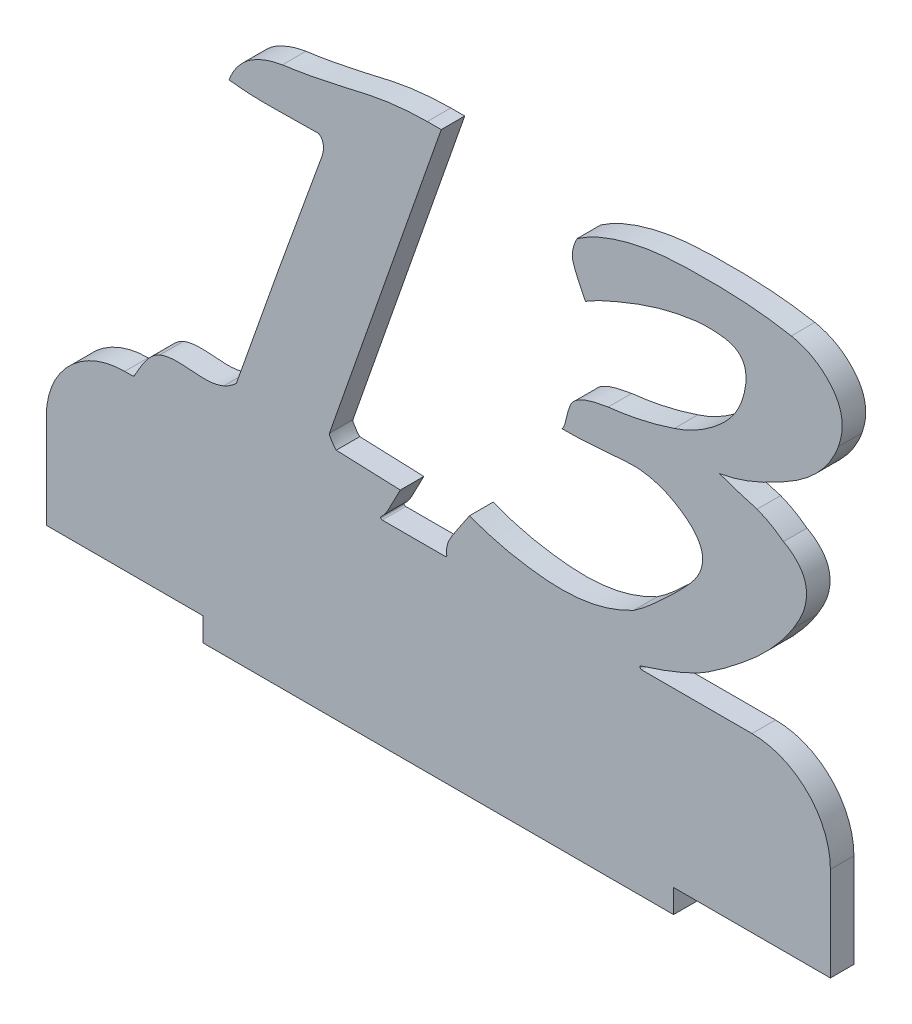
SolidWorks part; units mm, degrees
ref_plane "Front Plane" through (0, 0, 0) normal (0, 0, 1) x (1, 0, 0)
ref_plane "Top Plane" through (0, 0, 0) normal (0, 1, 0) x (1, 0, 0)
ref_plane "Right Plane" through (0, 0, 0) normal (1, 0, 0) x (0, 0, -1)
sketch "Sketch1" plane through (0, 0, 0) normal (0, 0, 1) x (1, 0, 0)
  line L0 (0, 20) -> (100, 20) construction
  line L1 (42.2093, 22) -> (51.1251, 22)
  line L2 (0, 22) -> (0, 0)
  line L3 (0, 0) -> (20, 0)
  line L4 (100, 22) -> (100, 0)
  line L5 (0, 22) -> (11.1488, 22)
  line L6 (90.1102, 22) -> (100, 22)
  line L7 (50.3695, 68.8865) -> (36.1201, 28.2493)
  line L8 (36.9802, 26.7833) -> (45.1506, 26.4705)
  line L9 (74.5438, 22) -> (90.1102, 22)
  line L11 (80, 0) -> (100, 0)
  line L13 (20, 0) -> (20, -3)
  line L14 (20, -3) -> (80, -3)
  line L15 (80, 0) -> (80, -3)
  spline S0 degree 3 poles (45.1506, 26.4705) (44.5557, 25.4573) (44.0105, 24.1351) (43.1126, 22.6689) (42.6125, 22.2566) (42.2988, 22.0538) (42.2093, 22) knots 0 0 0 0 0.504343 0.619768 0.735364 0.780343 0.780343 0.780343 0.780343
  spline S1 degree 3 poles (11.1488, 22) (11.2941, 22.2364) (11.6816, 22.909) (12.5467, 24.461) (13.5414, 25.6306) (14.4821, 26.06) knots 0.109992 0.109992 0.109992 0.109992 0.248912 0.498933 1 1 1 1
  spline S2 degree 3 poles (14.4821, 26.06) (15.8235, 26.5793) (18.5742, 26.3045) (21.3436, 26.1489) (22.6526, 26.7246) knots 0 0 0 0 0.501452 1 1 1 1
  spline S3 degree 2 poles (22.6526, 26.7246) (23.5341, 27.1151) (24.2358, 27.7801) knots 0 0 0 1 1 1
  spline S4 degree 3 poles (24.2358, 27.7801) (26.0181, 32.8153) (29.5431, 42.9381) (33.2322, 53.0023) (35.0646, 58.0577) knots 0 0 0 0 0.498323 1 1 1 1
  spline S5 degree 3 poles (35.0646, 58.0577) (35.2478, 58.5552) (35.543, 59.5218) (35.0904, 60.4332) (34.7323, 60.6378) knots 0 0 0 0 0.581397 1 1 1 1
  spline S6 degree 3 poles (34.7323, 60.6378) (32.8156, 60.6716) (29.0106, 60.4877) (25.1976, 60.5925) (23.3172, 60.8333) knots 0 0 0 0 0.503015 1 1 1 1
  spline S7 degree 3 poles (23.3172, 60.8333) (23.5491, 61.5005) (24.0334, 62.4494) (24.9514, 63.5102) (25.7246, 64.2327) (26.6726, 64.7864) (28.0996, 65.4691) (29.2917, 65.7839) (30.1194, 65.9154) knots 0 0 0 0 0.237267 0.352024 0.469659 0.590381 0.718477 1 1 1 1
  spline S8 degree 3 poles (30.1194, 65.9154) (33.2316, 66.3138) (37.0934, 67.1658) (41.7152, 68.2457) (44.7951, 68.7281) (47.0882, 68.8757) (48.5908, 68.8865) knots 0 0 0 0 0.501478 0.63281 0.759518 1 1 1 1
  spline S9 degree 3 poles (48.5908, 68.8865) (48.7993, 68.8865) (49.3922, 68.8865) (49.9851, 68.8865) (50.3695, 68.8865) knots 0 0 0 0 0.351648 1 1 1 1
  spline S10 degree 3 poles (36.1201, 28.2493) (36.067, 28.0495) (36.3986, 27.5398) (36.6763, 27.057) (36.9802, 26.7833) knots 0 0 0 0 0.324502 1 1 1 1
  spline S11 degree 3 poles (82.9341, 25.1414) (80.7325, 24.0584) (77.9268, 23.0044) (75.0619, 22.1485) (74.5438, 22) knots 0 0 0 0 0.226937 0.276837 0.276837 0.276837 0.276837
  spline S12 degree 3 poles (51.1251, 22) (51.0547, 22.2702) (51.0102, 22.8813) (51.2413, 23.8454) (52.269, 25.5907) (53.2802, 26.9397) (53.9857, 28.0538) knots 0.116796 0.116796 0.116796 0.116796 0.224396 0.348057 0.492967 1 1 1 1
  spline S13 degree 3 poles (53.9857, 28.0538) (55.6418, 27.4135) (58.2064, 26.6336) (61.7469, 26.0525) (64.4546, 25.7544) (67.1855, 25.7646) (70.7671, 26.2541) (73.316, 27.2091) (74.9004, 28.0538) knots 0 0 0 0 0.247125 0.371259 0.498796 0.625702 0.750177 1 1 1 1
  spline S14 degree 3 poles (74.9004, 28.0538) (75.9848, 28.7739) (77.5962, 30.1685) (79.8519, 32.2751) (81.4483, 33.8815) (82.6707, 35.2661) (83.3223, 36.3342) (83.6754, 37.3835) (83.7521, 38.408) (83.4899, 39.4037) (82.7121, 40.7534) (81.7368, 41.5413) (81.038, 42.0295) knots 0 0 0 0 0.209311 0.343078 0.497575 0.574369 0.640302 0.697767 0.75143 0.8034 0.861248 1 1 1 1
  spline S15 degree 3 poles (81.038, 42.0295) (79.9383, 42.7867) (78.1212, 43.6516) (75.4978, 44.0957) (71.6002, 43.8951) (68.389, 43.4795) (65.7918, 43.5542) knots 0 0 0 0 0.255382 0.379223 0.505212 1 1 1 1
  spline S16 degree 3 poles (65.7918, 43.5542) (66.0945, 43.9889) (66.3583, 45.0308) (66.5731, 46.0737) (66.7886, 46.5839) knots 0 0 0 0 0.48539 1 1 1 1
  spline S17 degree 3 poles (66.7886, 46.5839) (67.045, 47.2711) (68.6414, 48.3914) (70.5108, 48.6797) (71.6557, 48.8904) knots 0 0 0 0 0.373078 1 1 1 1
  spline S18 degree 2 poles (71.6557, 48.8904) (75.9814, 49.349) (80.0998, 50.7473) knots 0 0 0 1 1 1
  spline S19 degree 3 poles (80.0998, 50.7473) (81.1569, 51.08) (82.7079, 51.7803) (84.6264, 53.043) (86.0287, 54.1597) (87.2795, 55.4424) (88.5883, 57.3982) (89.0773, 59.1008) (89.2085, 60.2469) knots 0 0 0 0 0.23911 0.365172 0.495269 0.625648 0.750534 1 1 1 1
  spline S20 degree 3 poles (89.2085, 60.2469) (89.2941, 61.0468) (89.1979, 62.3947) (87.9779, 63.53) (86.7951, 63.9236) (85.4344, 64.0548) (83.9336, 64.1181) (82.3137, 63.9278) (80.0025, 63.5426) (77.0415, 62.7568) (74.1805, 61.6945) (72.0493, 60.7708) (70.4162, 60.0621) (69.3641, 59.4826) (68.7628, 59.1132) knots 0 0 0 0 0.105861 0.151148 0.202066 0.259997 0.323223 0.39085 0.464935 0.618432 0.775801 0.848984 0.911075 1 1 1 1
  spline S21 degree 3 poles (68.7628, 59.1132) (68.2875, 60.144) (67.5917, 61.3666) (67.0759, 62.9793) (67.099, 64.1495) (67.4141, 64.9917) (67.7073, 65.5245) knots 0 0 0 0 0.496027 0.61423 0.7339 1 1 1 1
  spline S22 degree 3 poles (67.7073, 65.5245) (69.5023, 66.7561) (72.6451, 68.037) (77.2188, 69.0058) (81.0332, 69.2777) (84.8696, 69.3237) (89.5517, 69.1887) (92.9035, 68.8191) (95.0138, 68.4174) knots 0 0 0 0 0.231433 0.359702 0.498958 0.639815 0.770266 1 1 1 1
  spline S23 degree 3 poles (95.0138, 68.4174) (96.0533, 68.2051) (97.5684, 67.6614) (99.2551, 66.3881) (100.3284, 65.2561) (101.1324, 63.9249) (101.6949, 61.8559) (101.3927, 60.2136) (101.0146, 59.1914) knots 0 0 0 0 0.252438 0.373944 0.498635 0.620593 0.739093 1 1 1 1
  spline S24 degree 3 poles (101.0146, 59.1914) (100.5211, 57.7837) (99.2709, 55.8094) (96.9349, 53.6135) (94.7531, 52.1752) (92.4468, 50.9303) (89.532, 49.575) (87.3101, 48.8879) (85.8465, 48.6363) knots 0 0 0 0 0.231688 0.359129 0.498309 0.638598 0.768407 1 1 1 1
  spline S25 degree 3 poles (85.8465, 48.6363) (86.7229, 48.3729) (88.2909, 47.7569) (89.918, 47.3232) (90.6549, 47.1116) knots 0 0 0 0 0.54394 1 1 1 1
  spline S26 degree 2 poles (90.6549, 47.1116) (92.4811, 46.4065) (94.0169, 45.1961) knots 0 0 0 1 1 1
  spline S27 degree 3 poles (94.0169, 45.1961) (94.7922, 44.7952) (95.7883, 44.0019) (96.6694, 42.6232) (96.9582, 41.5132) (96.9684, 40.3165) (96.5864, 38.4768) (95.8429, 37.1635) (95.2875, 36.2829) knots 0 0 0 0 0.250144 0.357669 0.464359 0.574792 0.698847 1 1 1 1
  spline S28 degree 3 poles (95.2875, 36.2829) (94.4678, 34.9837) (93.0086, 33.1373) (90.7475, 30.8744) (88.8631, 29.2844) (87.0389, 27.8497) (85.0947, 26.4451) (83.7616, 25.565) (82.9341, 25.1414) knots 0 0 0 0 0.274285 0.419249 0.571241 0.71478 0.834078 1 1 1 1
  dimension "D1" = 100
  dimension "D2" = 3
  dimension "D3" = 20
  dimension "D4" = 20
  dimension "D5" = 20
extrude "Boss-Extrude1" add sketch "Sketch1" along normal blind 3
fillet "Fillet1" radius 10 2 edges at (0, 22, 1.5) (100, 22, 1.5)
fillet "Fillet2" radius 0.2 4 edges at (74.5438, 22, 1.5) (42.2093, 22, 1.5) (51.1251, 22, 1.5) (11.1488, 22, 1.5)
